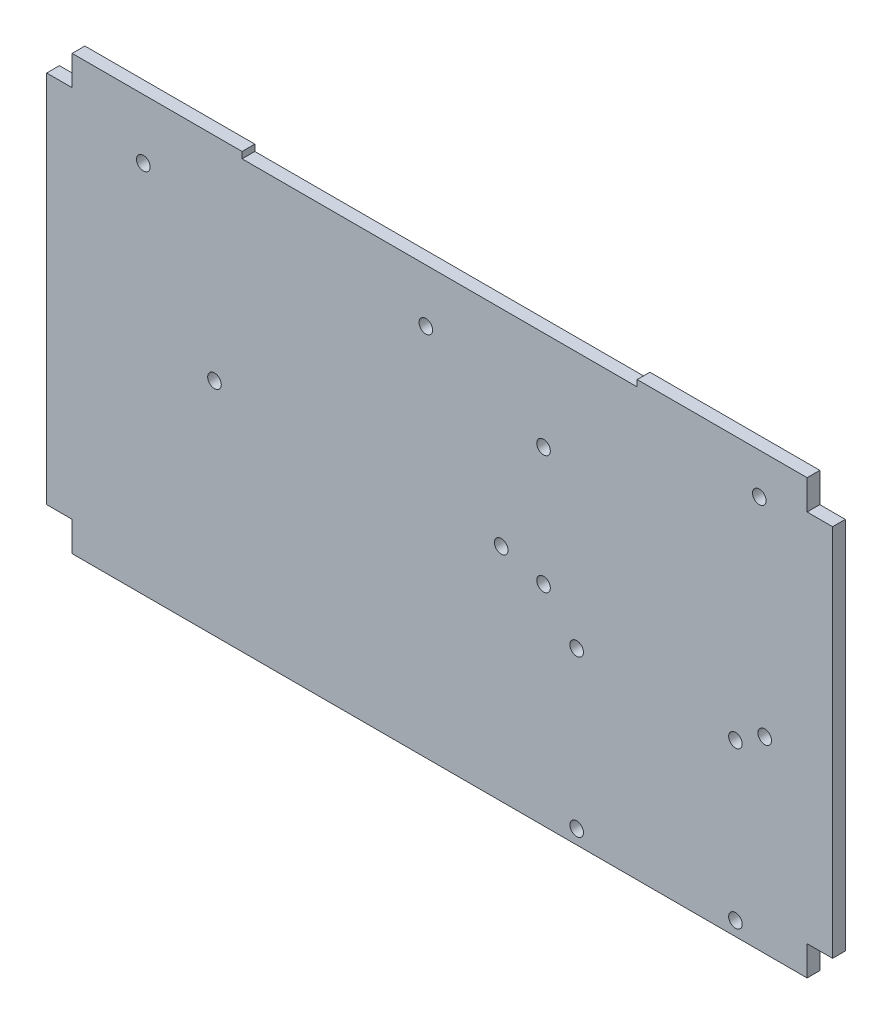
SolidWorks part; units mm, degrees
material "Сосна"
ref_plane "Спереди" through (0, 0, 0) normal (0, 0, 1) x (1, 0, 0)
ref_plane "Сверху" through (0, 0, 0) normal (0, 1, 0) x (1, 0, 0)
ref_plane "Справа" through (0, 0, 0) normal (1, 0, 0) x (0, 0, -1)
sketch "Эскиз1" plane through (0, 0, 0) normal (0, 0, 1) x (1, 0, 0)
  line L8 (92.5, -51) -> (92.5, -48.699)
  line L9 (92.5, 51) -> (-92.5, 51)
  line L10 (-92.5, 51) -> (-92.5, 48.699)
  line L11 (-92.5, -51) -> (92.5, -51)
  line L16 (92.5, -51) -> (92.5, -48.699)
  line L17 (92.5, 51) -> (-92.5, 51)
  line L18 (-92.5, 51) -> (-92.5, 48.699)
  line L19 (-92.5, -51) -> (92.5, -51)
  line L32 (-92.5, 46.301) -> (-92.5, -46.301)
  line L33 (-92.5, 46.301) -> (-92.5, -46.301)
  line L34 (-92.5, -48.699) -> (-92.5, -51)
  line L35 (-92.5, -48.699) -> (-92.5, -51)
  line L36 (92.5, -46.301) -> (92.5, 46.301)
  line L37 (92.5, -46.301) -> (92.5, 46.301)
  line L38 (92.5, 48.699) -> (92.5, 51)
  line L39 (92.5, 48.699) -> (92.5, 51)
  arc A8 (-92.5, 46.301) -> (-92.5, 48.699) centre (-89.75, 47.5) ccw
  arc A9 (-92.5, 46.301) -> (-92.5, 48.699) centre (-89.75, 47.5) ccw
  arc A10 (-92.5, -48.699) -> (-92.5, -46.301) centre (-89.75, -47.5) ccw
  arc A11 (-92.5, -48.699) -> (-92.5, -46.301) centre (-89.75, -47.5) ccw
  arc A12 (92.5, -46.301) -> (92.5, -48.699) centre (89.75, -47.5) ccw
  arc A13 (92.5, -46.301) -> (92.5, -48.699) centre (89.75, -47.5) ccw
  arc A14 (92.5, 48.699) -> (92.5, 46.301) centre (89.75, 47.5) ccw
  arc A15 (92.5, 48.699) -> (92.5, 46.301) centre (89.75, 47.5) ccw
  dimension "D1" = 0
extrude "Бобышка-Вытянуть1" add sketch "Эскиз1" along normal blind 3 contours L19 L16 A13 L37 A15 L39 L17 L18 A9 L33 A11 L35
hole_wizard "Отверстие с зазором M31" positions "Эскиз4" profile "Эскиз5" hole size "M3" standard "ISO" end condition up to next
sketch "Эскиз4" plane through (0, 0, 0) normal (0, 0, -1) x (-1, 0, 0)
  point P0 (-76.53, -6.8)
  point P3 (-24.46, -1.72)
  point P6 (-24.46, 26.22)
  point P9 (-75.26, 41.46)
  point P12 (-69.6363, -47.6857)
  point P15 (-69.6363, -10.9439)
  point P18 (-32.2568, -10.9439)
  point P21 (-32.2568, -47.6857)
  point P24 (-14.5, 1)
  point P27 (53, 1)
  point P38 (3.25, 37)
  point P41 (69.75, 37)
sketch "Эскиз5" plane through (76.53, -6.8, 0) normal (1, 0, 0) x (0, 1, 0)
  line L0 (0, 0) -> (0, 3)
  line L1 (0, 3) -> (1.6, 3)
  line L2 (1.6, 3) -> (1.6, 0)
  line L5 (1.6, 0) -> (0, 0)
  line L11 (0, -6.35) -> (0, 107.95) construction
  dimension "Диаметр сквозного отверстия" = 3.2
  dimension "Глубина сквозного отверстия" = 3
sketch "Эскиз6" plane through (0, 0, 0) normal (0, 0, -1) x (-1, 0, 0)
  line L0 (0, 0) -> (50000, 0) construction
  line L1 (-93, 51) -> (-86.5, 51)
  line L2 (-93, 51) -> (-93, 44)
  line L3 (-93, 44) -> (-86.5, 44)
  line L4 (-86.5, 51) -> (-86.5, 44)
  line L5 (-89.75, 44) -> (-89.75, 51) construction
  line L6 (-93, 47.5) -> (-86.5, 47.5) construction
  line L7 (0, 0) -> (0, -50000) construction
  line L8 (93, 47.5) -> (86.5, 47.5) construction
  line L9 (89.75, 44) -> (89.75, 51) construction
  line L10 (86.5, 51) -> (86.5, 44)
  line L11 (93, 44) -> (86.5, 44)
  line L12 (93, 51) -> (93, 44)
  line L13 (93, 51) -> (86.5, 51)
  line L14 (89.75, -44) -> (89.75, -51) construction
  line L15 (93, -47.5) -> (86.5, -47.5) construction
  line L16 (-93, -47.5) -> (-86.5, -47.5) construction
  line L17 (-89.75, -44) -> (-89.75, -51) construction
  line L18 (93, -51) -> (86.5, -51)
  line L19 (93, -51) -> (93, -44)
  line L20 (93, -44) -> (86.5, -44)
  line L21 (86.5, -51) -> (86.5, -44)
  line L22 (-86.5, -51) -> (-86.5, -44)
  line L23 (-93, -44) -> (-86.5, -44)
  line L24 (-93, -51) -> (-93, -44)
  line L25 (-93, -51) -> (-86.5, -51)
  point P5 (-89.75, 47.5)
  point P17 (89.75, 47.5)
  point P34 (-89.75, -47.5)
  point P35 (89.75, -47.5)
  point P68 (-89.75, 47.5)
extrude "Вырез-Вытянуть1" cut sketch "Эскиз6" against normal through all
sketch "Эскиз7" plane through (0, 0, 0) normal (0, 0, -1) x (-1, 0, 0)
  line L0 (-86.5, 51) -> (86.5, 51) construction
  line L1 (-46.5, 51) -> (46.5, 51)
  line L2 (-46.5, 51) -> (-46.5, 49.5)
  line L3 (-46.5, 49.5) -> (46.5, 49.5)
  line L4 (46.5, 51) -> (46.5, 49.5)
  line L5 (0, 49.5) -> (0, 51) construction
  line L6 (-46.5, 50.25) -> (46.5, 50.25) construction
  point P104 (0, 50.25)
  dimension "D1" = 93
  dimension "D2" = 1.5
extrude "Вырез-Вытянуть2" cut sketch "Эскиз7" against normal through all contours L3 L4 L1 L2
equation "\"D1@Бобышка-Вытянуть1@G1025BF, Корпус для РЭА 225х113х63мм, пластик, черный с крепежным фланцем-1.Part\"=57.5-4"
